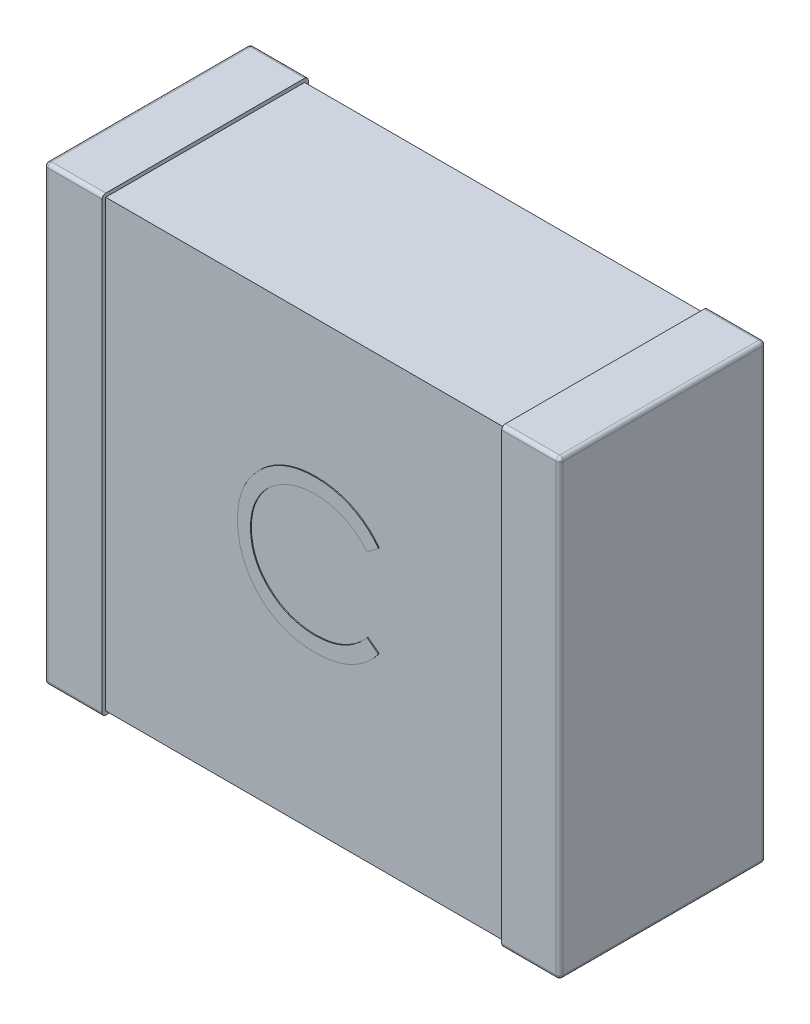
SolidWorks part; units mm, degrees
ref_plane "前视基准面" through (0, 0, 0) normal (0, 0, 1) x (1, 0, 0)
ref_plane "上视基准面" through (0, 0, 0) normal (0, 1, 0) x (1, 0, 0)
ref_plane "右视基准面" through (0, 0, 0) normal (1, 0, 0) x (0, 0, -1)
sketch "草图3" plane through (0, 0, 0) normal (0, 0, 1) x (1, 0, 0)
  line L0 (0, 4.2576) -> (0, -4.4067) construction
  line L1 (-2.85, 2.5) -> (-2.21, 2.5)
  line L2 (-2.85, 2.5) -> (-2.85, -2.5)
  line L3 (-2.85, -2.5) -> (-2.21, -2.5)
  line L4 (-2.21, 2.5) -> (-2.21, -2.5)
  line L5 (-2.85, 2.5) -> (-2.21, -2.5) construction
  line L6 (-2.85, -2.5) -> (-2.21, 2.5) construction
  line L7 (2.85, -2.5) -> (2.21, 2.5) construction
  line L8 (2.85, 2.5) -> (2.21, -2.5) construction
  line L9 (2.21, 2.5) -> (2.21, -2.5)
  line L10 (2.85, -2.5) -> (2.21, -2.5)
  line L11 (2.85, 2.5) -> (2.85, -2.5)
  line L12 (2.85, 2.5) -> (2.21, 2.5)
  point P0 (-2.53, 0)
  point P12 (2.53, 0)
  dimension "D1" = 0.64
  dimension "D2" = 5
  dimension "D3" = 2.85
extrude "凸台-拉伸1" add sketch "草图3" along normal blind 2.24 and the other way blind 0.04
sketch "草图5" plane through (0, 0, 0) normal (1, 0, 0) x (0, 0, -1)
  line L0 (0, 2.46) -> (0, -2.46)
  line L1 (0, -2.46) -> (-2.2, -2.46)
  line L2 (-2.2, -2.46) -> (-2.2, 2.46)
  line L3 (-2.2, 2.46) -> (0, 2.46)
  dimension "D1" = 4.92
  dimension "D2" = 2.2
extrude "凸台-拉伸3" add sketch "草图5" along normal mid plane 4.52
fillet "圆角3" radius 0.04 16 edges at (2.85, 0, -0.04) (2.85, -2.5, 1.1) (2.85, 0, 2.24) (2.85, 2.5, 1.1) (-2.85, 0, -0.04) (-2.85, 2.5, 1.1) (-2.85, 0, 2.24) (-2.85, -2.5, 1.1) (2.53, 2.5, -0.04) (2.53, -2.5, -0.04) (2.53, -2.5, 2.24) (2.53, 2.5, 2.24) (-2.53, -2.5, -0.04) (-2.53, -2.5, 2.24) (-2.53, 2.5, -0.04) (-2.53, 2.5, 2.24)
sketch "草图6" plane through (0, 0, 2.2) normal (0, 0, 1) x (1, 0, 0)
  text T0 "C" font "Century Gothic" height 1.6
extrude "凸台-拉伸4" add sketch "草图6" along normal blind 0.01
